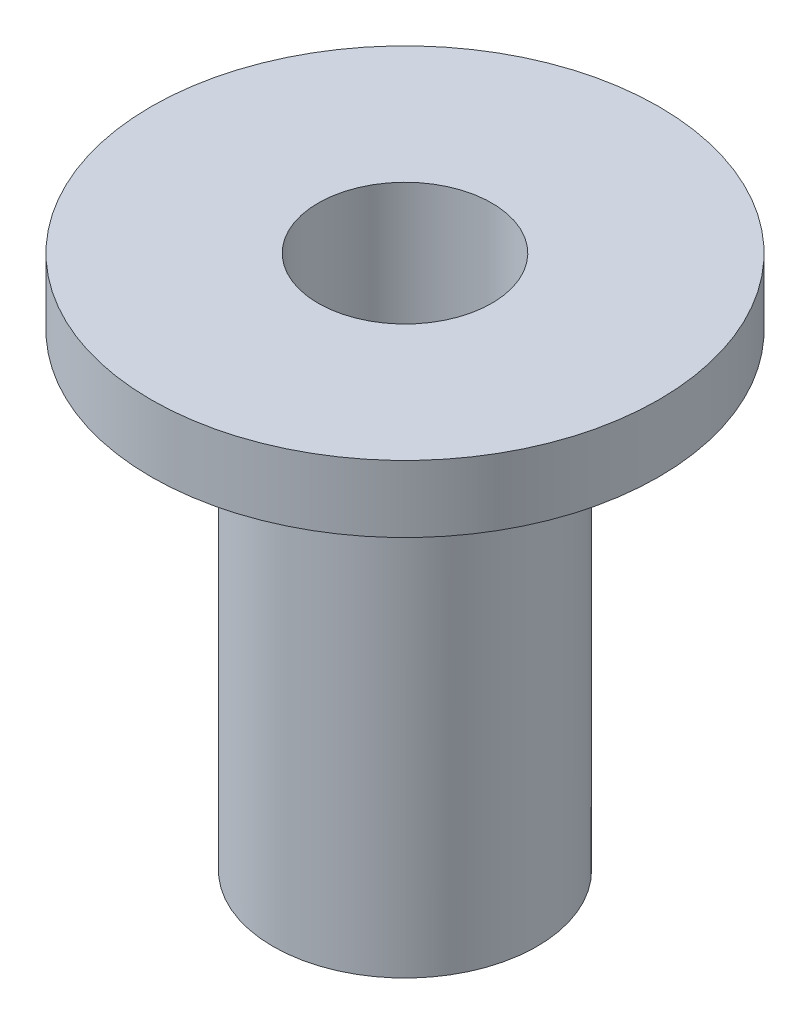
SolidWorks part; units mm, degrees
ref_plane "Front Plane" through (0, 0, 0) normal (0, 0, 1) x (1, 0, 0)
ref_plane "Top Plane" through (0, 0, 0) normal (0, 1, 0) x (1, 0, 0)
ref_plane "Right Plane" through (0, 0, 0) normal (1, 0, 0) x (0, 0, -1)
sketch "Sketch1" plane through (0, 0, 0) normal (0, 0, 1) x (1, 0, 0)
  line L0 (0, 5.1734) -> (0, -5.1734) construction
  line L8 (-2.6, 0) -> (-2.6, 16)
  line L9 (-2.6, 16) -> (-7.6, 16)
  line L10 (-7.6, 16) -> (-7.6, 14)
  line L11 (-7.6, 14) -> (-3.95, 14)
  line L12 (-3.95, 14) -> (-3.95, 0)
  line L13 (-3.95, 0) -> (-2.6, 0)
  point P4 (0, 0)
  dimension "D1" = 2.6
  dimension "D2" = 3.95
  dimension "D3" = 5
  dimension "D4" = 2
  dimension "D5" = 14
revolve "Revolve1" add sketch "Sketch1" angle 360 about L0
chamfer "Chamfer1" distance 0.5 angle 45 1 edges at (0, 14, 3.95)
